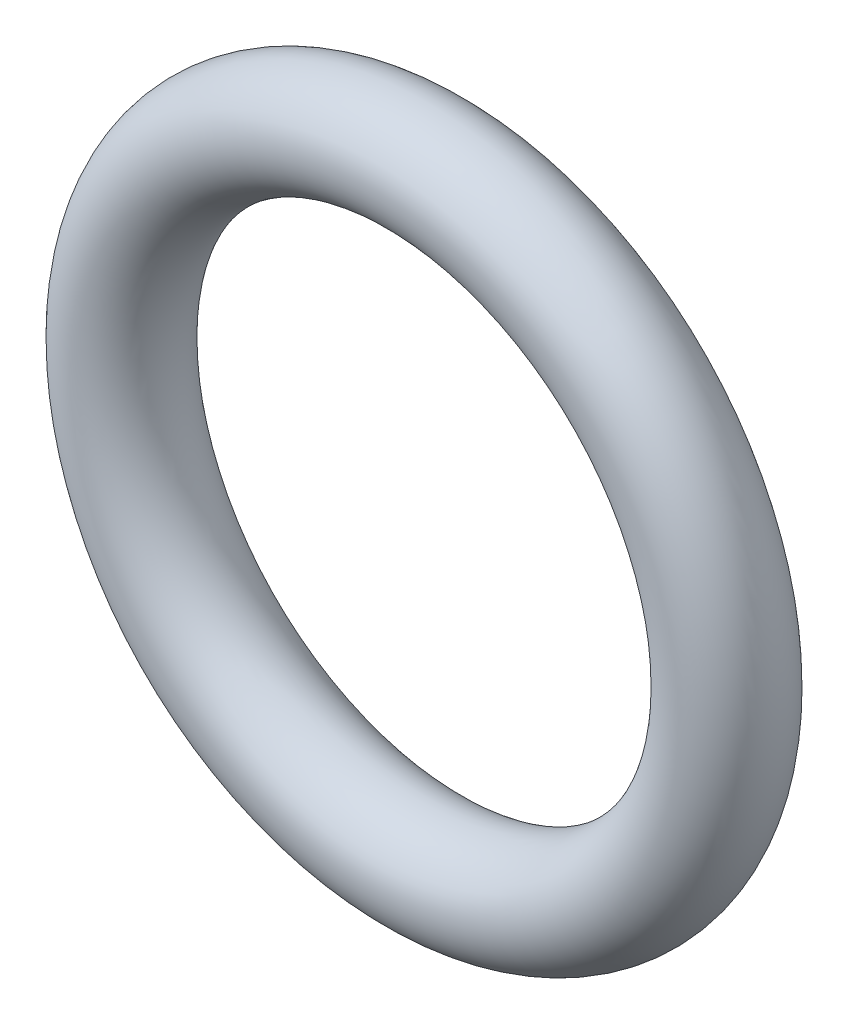
SolidWorks part; units mm, degrees
ref_plane "Front Plane" through (0, 0, 0) normal (0, 0, 1) x (1, 0, 0)
ref_plane "Top Plane" through (0, 0, 0) normal (0, 1, 0) x (1, 0, 0)
ref_plane "Right Plane" through (0, 0, 0) normal (1, 0, 0) x (0, 0, -1)
sketch "Sketch1" plane through (0, 0, 0) normal (0, 1, 0) x (1, 0, 0)
  line L0 (0, 0) -> (0, 11.5476) construction
  circle A0 centre (4.25, 0) radius 0.75
  point P5 (3.5, 0)
  point P6 (5, 0)
  dimension "D1" = 3.5
  dimension "D2" = 5
revolve "Revolve1" add sketch "Sketch1" angle 360 about L0
sketch "Sketch2" plane through (0, 0, 0) normal (0, 0, 1) x (1, 0, 0)
  circle A0 centre (0, 0) radius 2.235
  circle A1 centre (0, 0) radius 4.015
